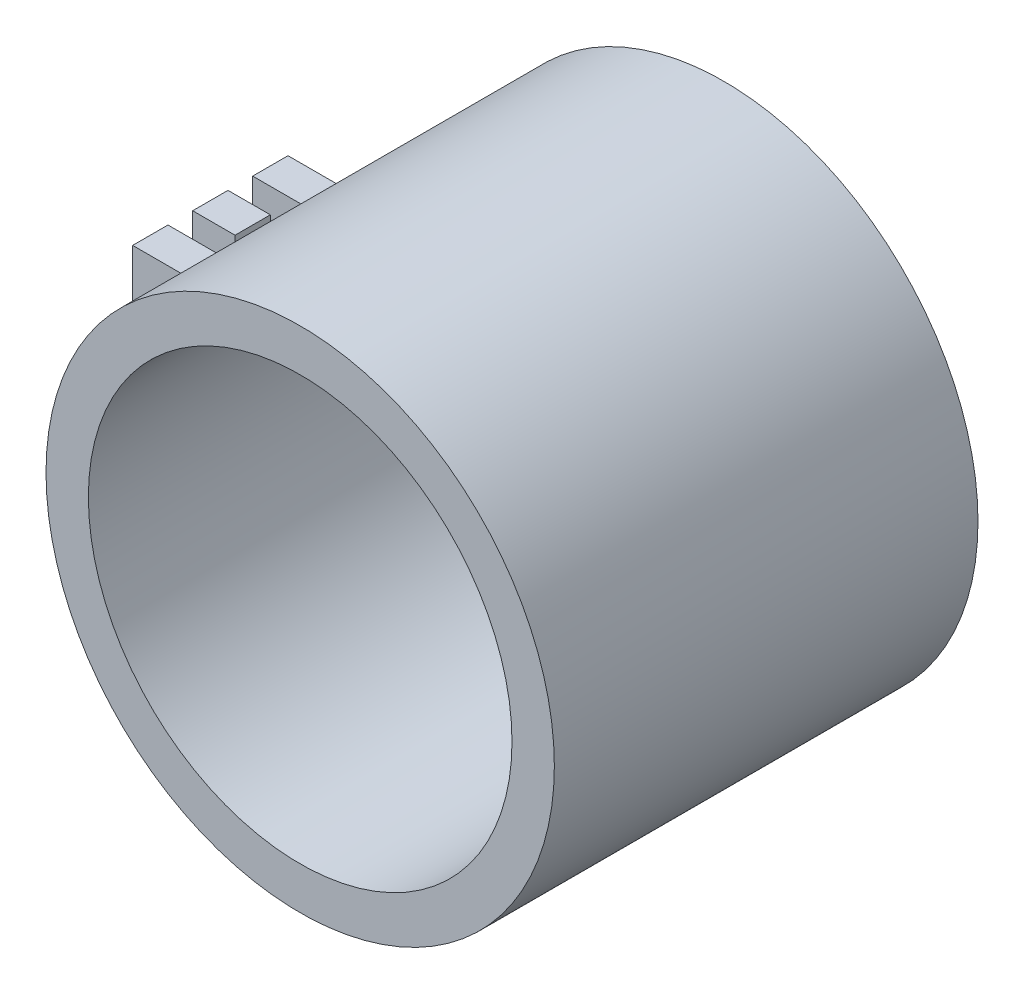
SolidWorks part; units mm, degrees
ref_plane "Front Plane" through (0, 0, 0) normal (0, 0, 1) x (1, 0, 0)
ref_plane "Top Plane" through (0, 0, 0) normal (0, 1, 0) x (1, 0, 0)
ref_plane "Right Plane" through (0, 0, 0) normal (1, 0, 0) x (0, 0, -1)
sketch "Sketch1" plane through (0, 0, 0) normal (0, 0, 1) x (1, 0, 0)
  circle A0 centre (0, 0) radius 36
  dimension "D1" = 72
extrude "Boss-Extrude1" add sketch "Sketch1" along normal blind 60
sketch "Sketch2" plane through (0, 0, 60) normal (0, 0, 1) x (1, 0, 0)
  circle A0 centre (0, 0) radius 30
  dimension "D1" = 60
extrude "Cut-Extrude1" cut sketch "Sketch2" against normal blind 60
sketch "Sketch3" plane through (0, 0, 60) normal (0, 0, 1) x (1, 0, 0)
  line L0 (0, 36) -> (0, 31.9) construction
  circle A0 centre (0, 0) radius 36 construction
  dimension "D1" = 4.1
ref_plane "Plane1" through (0, 0, 30) normal (0, 0, 1) x (1, 0, 0)
sketch "Sketch4" plane through (0, 0, 30) normal (0, 0, 1) x (1, 0, 0)
  line L0 (-49.6206, 0) -> (48.4024, 0) construction
  line L1 (-32.7261, 15) -> (-42.7261, 15) construction
  circle A0 centre (0, 0) radius 36 construction
  circle A1 centre (0, 0) radius 36 construction
  dimension "D1" = 10
  dimension "D2" = 15
ref_plane "Plane2" through (0, 0, 24) normal (0, 0, 1) x (1, 0, 0)
ref_plane "Plane3" through (0, 0, 36) normal (0, 0, 1) x (1, 0, 0)
sketch "Sketch5" plane through (0, 0, 24) normal (0, 0, 1) x (1, 0, 0)
  line L0 (-32.7261, 15) -> (-42.7261, 15) construction
  line L1 (-32.7261, 15) -> (-42.7261, 15)
  line L3 (-42.7261, 15) -> (-42.7261, 0)
  line L4 (-42.7261, 0) -> (-42.7261, -6)
  line L5 (-36.7261, 11.7264) -> (-36.7261, -6)
  line L6 (-42.7261, -6) -> (-36.7261, -6)
  line L7 (-34.0366, 11.7264) -> (-36.7261, 11.7264)
  circle A0 centre (0, 0) radius 36 construction
  arc A1 (-32.7261, 15) -> (-34.0366, 11.7264) centre (0, 0) ccw
  dimension "D1" = 15
  dimension "D2" = 6
  dimension "D3" = 17.7264
  dimension "D4" = 2.6895
extrude "Boss-Extrude2" add sketch "Sketch5" against normal blind 5
mirror "Mirror1" about plane through (0, 0, 30) normal (0, 0, 1) of "Boss-Extrude2"
sketch "Sketch6" plane through (0, 0, 30) normal (0, 0, 1) x (1, 0, 0)
  line L4 (-42.7261, 15) -> (-42.7261, -6) construction
  line L8 (-36.7261, 15) -> (-42.7261, 15)
  line L9 (-42.7261, 15) -> (-42.7261, -6)
  line L10 (-42.7261, 15) -> (-42.7261, -6) construction
  line L11 (-32.7261, -6) -> (-42.7261, -6)
  line L13 (-36.7261, -2.7264) -> (-34.0366, -2.7264)
  line L14 (-36.7261, 15) -> (-36.7261, -2.7264)
  line L15 (-42.7261, 15) -> (-36.7261, 15) construction
  arc A2 (-32.7261, -6) -> (-34.0366, -2.7264) centre (0, 9) cw
  circle A3 centre (0, 0) radius 36 construction
  dimension "D5" = 36
  dimension "D1" = 2.6895
  dimension "D2" = 6
  dimension "D3" = 17.7264
  dimension "D4" = 10
  dimension "D6" = 3.2736
  dimension "D7" = 36.7261
extrude "Boss-Extrude4" add sketch "Sketch6" along normal blind 2.5 and the other way blind 2.5
sketch "Sketch7" plane through (0, 0, 41) normal (0, 0, 1) x (1, 0, 0)
  line L0 (-36.7261, 11.7264) -> (-36.7261, 15) construction
  line L1 (-32.7261, 15) -> (-42.7261, 15) construction
  line L2 (-36.7261, 15) -> (-42.7261, 15) construction
  line L3 (-39.7261, 15) -> (-39.7261, -6) construction
  line L4 (-42.7261, -6) -> (-36.7261, -6) construction
  circle A0 centre (-39.7261, -1) radius 2.5
  dimension "D1" = 5
  dimension "D2" = 5
extrude "Cut-Extrude2" cut sketch "Sketch7" against normal through all
